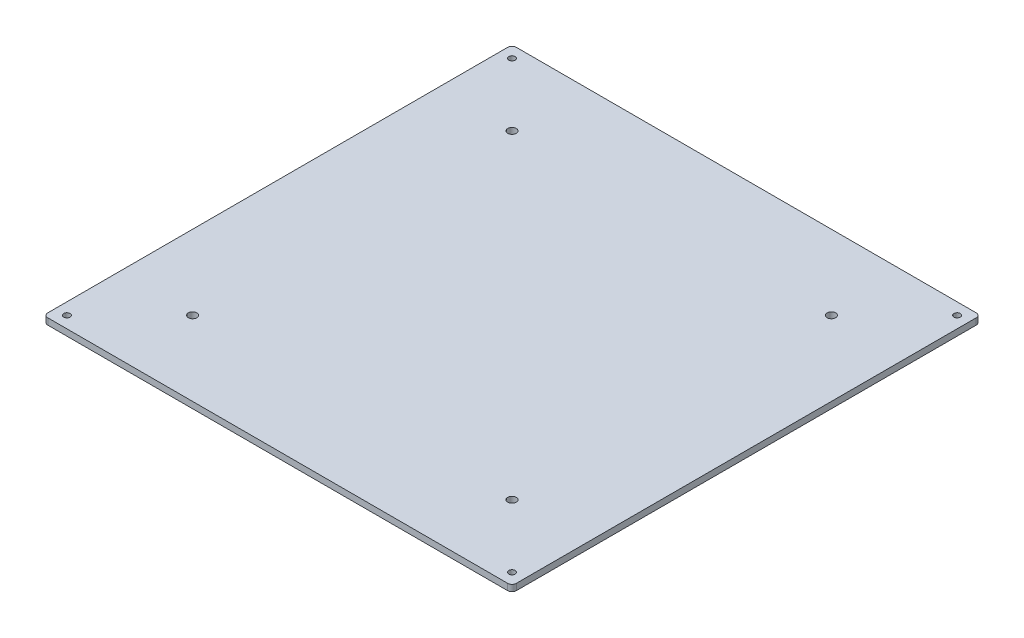
SolidWorks part; units mm, degrees
material "1060 Alloy"
ref_plane "Front Plane" through (0, 0, 0) normal (0, 0, 1) x (1, 0, 0)
ref_plane "Top Plane" through (0, 0, 0) normal (0, 1, 0) x (1, 0, 0)
ref_plane "Right Plane" through (0, 0, 0) normal (1, 0, 0) x (0, 0, -1)
sketch "Sketch1" plane through (0, 0, 0) normal (0, 1, 0) x (1, 0, 0)
  line L1 (110, -110) -> (-110, -110)
  line L2 (110, -110) -> (110, 110)
  line L3 (110, 110) -> (-110, 110)
  line L4 (-110, -110) -> (-110, 110)
  line L5 (110, -110) -> (-110, 110) construction
  line L6 (110, 110) -> (-110, -110) construction
  point P0 (0, 0)
  dimension "D1" = 220
  dimension "D2" = 220
extrude "Boss-Extrude1" add sketch "Sketch1" along normal blind 3
sketch "Sketch3" plane through (0, 3, 0) normal (0, 1, 0) x (1, 0, 0)
  line L0 (110, 110) -> (-110, 110) construction
  line L1 (-75, -75) -> (75, -75) construction
  line L2 (-75, -75) -> (-75, 75) construction
  line L3 (-75, 75) -> (75, 75) construction
  line L4 (75, -75) -> (75, 75) construction
  line L5 (-75, -75) -> (75, 75) construction
  line L6 (-75, 75) -> (75, -75) construction
  line L7 (110, -110) -> (110, 110) construction
  line L8 (110, 110) -> (-110, 110) construction
  line L9 (-104.5, -104.5) -> (104.5, -104.5) construction
  line L10 (-104.5, -104.5) -> (-104.5, 104.5) construction
  line L11 (-104.5, 104.5) -> (104.5, 104.5) construction
  line L12 (104.5, -104.5) -> (104.5, 104.5) construction
  line L13 (-104.5, -104.5) -> (104.5, 104.5) construction
  line L14 (-104.5, 104.5) -> (104.5, -104.5) construction
  line L15 (110, -110) -> (110, 110) construction
  circle A0 centre (-75, 75) radius 2
  circle A1 centre (75, 75) radius 2
  circle A2 centre (75, -75) radius 2
  circle A3 centre (-75, -75) radius 2
  circle A4 centre (-104.5, 104.5) radius 1.5
  circle A5 centre (104.5, 104.5) radius 1.5
  circle A6 centre (104.5, -104.5) radius 1.5
  circle A7 centre (-104.5, -104.5) radius 1.5
  point P0 (0, 0)
  point P14 (0, 0)
  dimension "D3" = 4
  dimension "D6" = 3
  dimension "D1" = 35
  dimension "D2" = 35
  dimension "D4" = 5.5
  dimension "D5" = 5.5
extrude "Cut-Extrude1" cut sketch "Sketch3" against normal blind 10
fillet "Fillet1" radius 2 4 edges at (-110, 1.5, -110) (110, 1.5, -110) (110, 1.5, 110) (-110, 1.5, 110)
sketch "Sketch2" plane through (0, 0, 0) normal (0, 1, 0) x (1, 0, 0)
  line L0 (0, -212.9179) -> (0, 212.9179) construction
  line L1 (-223.4465, 0) -> (223.4465, 0) construction
  point P4 (0, 0)
  point P8 (0, 0)
